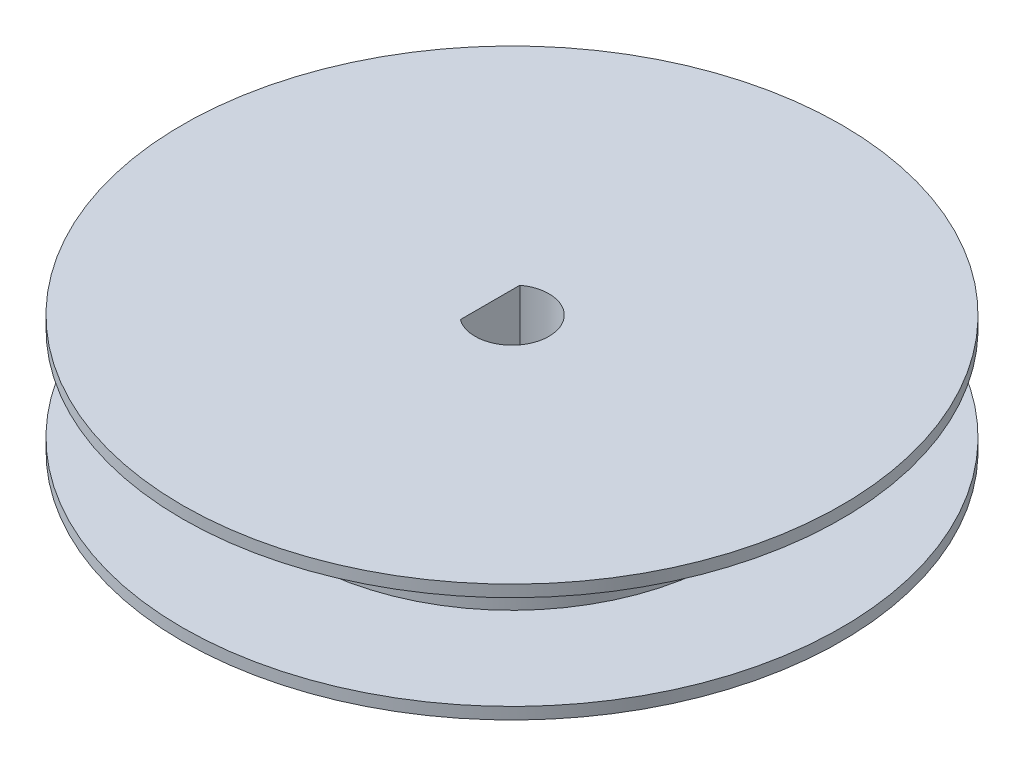
SolidWorks part; units mm, degrees
ref_plane "前基準面" through (0, 0, 0) normal (0, 0, 1) x (1, 0, 0)
ref_plane "上基準面" through (0, 0, 0) normal (0, 1, 0) x (1, 0, 0)
ref_plane "右基準面" through (0, 0, 0) normal (1, 0, 0) x (0, 0, -1)
sketch "草圖1" plane through (0, 0, 0) normal (0, 1, 0) x (1, 0, 0)
  circle A0 centre (0, 0) radius 9
  dimension "D1" = 18
extrude "填料-伸長1" add sketch "草圖1" along normal blind 5
sketch "草圖2" plane through (0, 5, 0) normal (0, 1, 0) x (1, 0, 0)
  line L1 (-0.93, -1.2649) -> (-0.93, 1.2649)
  circle A0 centre (0, 0) radius 1.57
extrude "除料-伸長1" cut sketch "草圖2" against normal through all contours L1 A0
sketch "草圖3" plane through (0, 5, 0) normal (0, 1, 0) x (1, 0, 0)
  circle A0 centre (0, 0) radius 14
  circle A1 centre (0, 0) radius 9
sketch "草圖5" plane through (0, 0, 0) normal (0, -1, 0) x (1, 0, 0)
  circle A0 centre (0, 0) radius 14
  circle A1 centre (0, 0) radius 9
sketch "草圖6" plane through (0, 0, 0) normal (1, 0, 0) x (0, 0, -1)
  circle A0 centre (-8.2974, 2.581) radius 0.4984
extrude "除料-伸長3" cut sketch "草圖6" against normal mid plane 100
extrude "填料-伸長2" add sketch "草圖3" against normal blind 0.5
extrude "填料-伸長3" add sketch "草圖5" against normal blind 0.5
